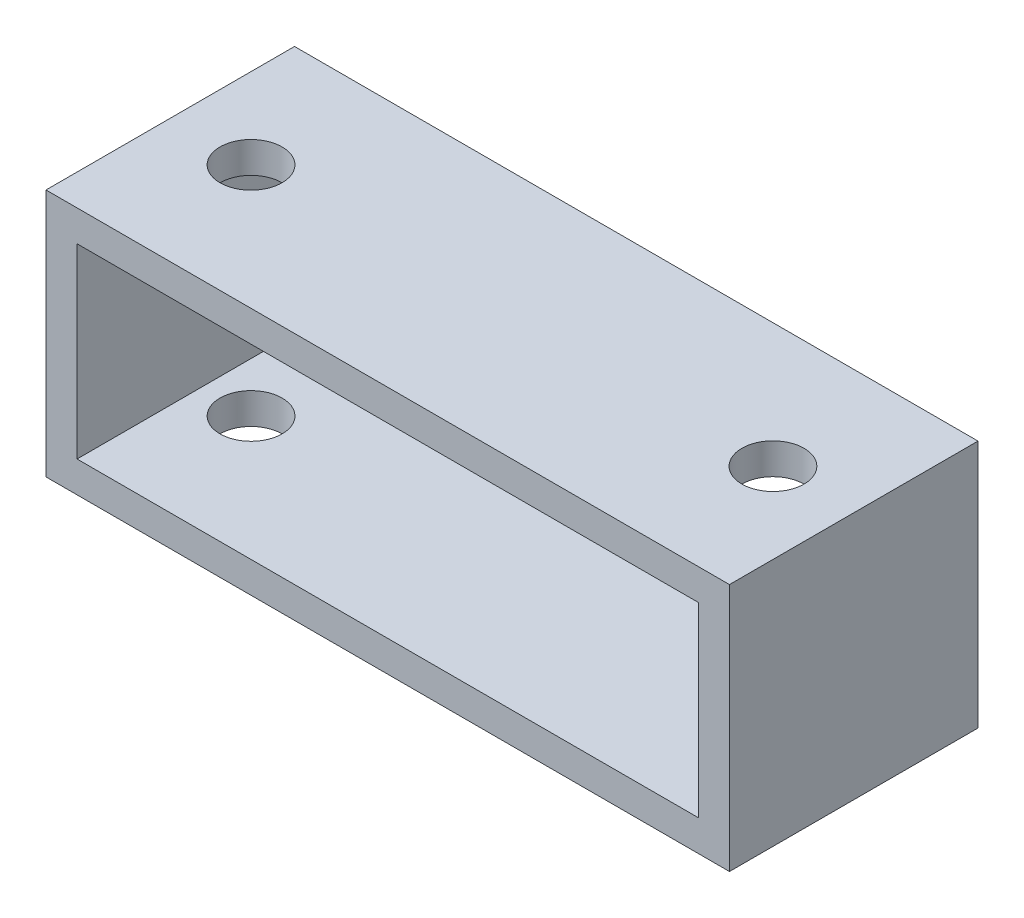
SolidWorks part; units mm, degrees
ref_plane "前视基准面" through (0, 0, 0) normal (0, 0, 1) x (1, 0, 0)
ref_plane "上视基准面" through (0, 0, 0) normal (0, 1, 0) x (1, 0, 0)
ref_plane "右视基准面" through (0, 0, 0) normal (1, 0, 0) x (0, 0, -1)
sketch "草图1" plane through (0, 0, 0) normal (0, 1, 0) x (1, 0, 0)
  line L1 (-27.5, -10) -> (27.5, -10)
  line L2 (-27.5, -10) -> (-27.5, 10)
  line L3 (-27.5, 10) -> (27.5, 10)
  line L4 (27.5, -10) -> (27.5, 10)
  line L5 (-27.5, -10) -> (27.5, 10) construction
  line L6 (-27.5, 10) -> (27.5, -10) construction
  point P0 (0, 0)
  dimension "D1" = 20
  dimension "D2" = 55
extrude "凸台-拉伸1" add sketch "草图1" along normal blind 20
sketch "草图2" plane through (0, 0, 10) normal (0, 0, 1) x (1, 0, 0)
  line L0 (-27.5, 10) -> (27.5, 10) construction
  line L1 (-27.5, 20) -> (-27.5, 0) construction
  line L2 (27.5, 20) -> (27.5, 0) construction
  line L3 (0, 0) -> (0, 20) construction
  line L4 (-27.5, 20) -> (27.5, 20) construction
  line L6 (-25, 2.5) -> (25, 2.5)
  line L7 (-25, 2.5) -> (-25, 17.5)
  line L8 (-25, 17.5) -> (25, 17.5)
  line L9 (25, 2.5) -> (25, 17.5)
  line L10 (-25, 2.5) -> (25, 17.5) construction
  line L11 (-25, 17.5) -> (25, 2.5) construction
  point P11 (0, 10)
  dimension "D1" = 50
  dimension "D2" = 15
extrude "切除-拉伸1" cut sketch "草图2" against normal up to next
sketch "草图3" plane through (0, 20, 0) normal (0, 1, 0) x (1, 0, 0)
  line L0 (-27.5, 0) -> (27.5, 0) construction
  line L1 (-27.5, 10) -> (-27.5, -10) construction
  line L2 (27.5, -10) -> (27.5, 10) construction
  circle A0 centre (-21, 0) radius 2.5
  circle A1 centre (21, 0) radius 2.5
  dimension "D3" = 5
  dimension "D4" = 5
  dimension "D1" = 6.5
  dimension "D2" = 6.5
extrude "切除-拉伸2" cut sketch "草图3" against normal up to surface (20 mm away) up to face at (0, 0, 0)
